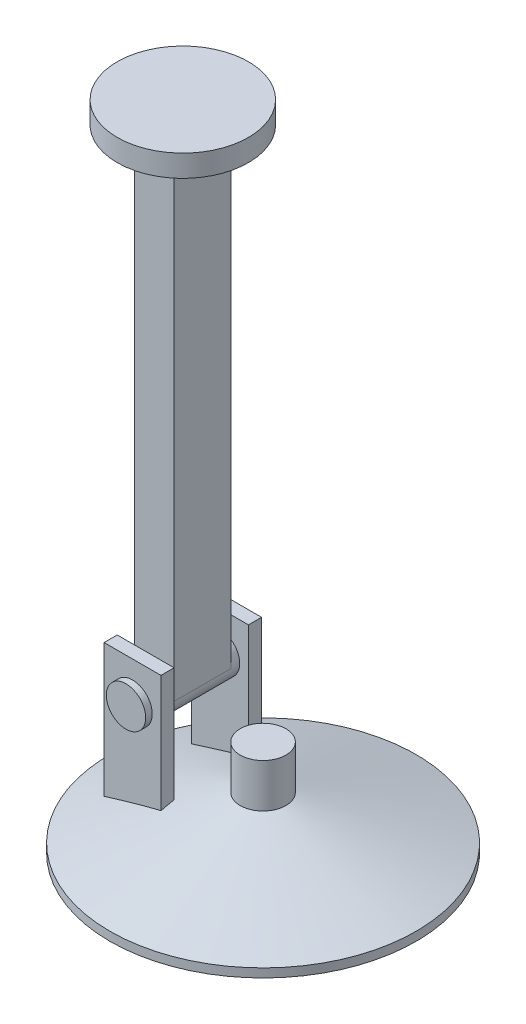
SolidWorks part; units mm, degrees
ref_plane "Front Plane" through (0, 0, 0) normal (0, 0, 1) x (1, 0, 0)
ref_plane "Top Plane" through (0, 0, 0) normal (0, 1, 0) x (1, 0, 0)
ref_plane "Right Plane" through (0, 0, 0) normal (1, 0, 0) x (0, 0, -1)
sketch "Sketch1" plane through (0, 0, 0) normal (0, 1, 0) x (1, 0, 0)
  circle A0 centre (0, 0) radius 35
  point P3 (0, 0)
  point P4 (0, 0)
  dimension "D1" = 70
ref_plane "Plane1" through (0, 10, 0) normal (0, 1, 0) x (1, 0, 0)
sketch "Sketch2" plane through (0, 10, 0) normal (0, 1, 0) x (1, 0, 0)
  circle A0 centre (0, 0) radius 5.2243
loft "Loft3" add profiles "Sketch1", "Sketch2"
sketch "Sketch8" plane through (0, 10, 0) normal (0, 1, 0) x (1, 0, 0)
  circle A0 centre (0, 0) radius 5.2243
extrude "Boss-Extrude1" add sketch "Sketch8" along normal blind 10
sketch "Sketch10" plane through (0, 0, 0) normal (0, 1, 0) x (1, 0, 0)
  circle A0 centre (0, 0) radius 35
ref_plane "Plane2" through (0, 0, 10) normal (0, 0, 1) x (1, 0, 0)
sketch "Sketch16" plane through (0, 0, 10) normal (0, 0, 1) x (1, 0, 0)
  line L0 (35, 0) -> (-35, 0) construction
  line L1 (-24.8409, 0) -> (-11.8409, 0)
  line L2 (-24.8409, 0) -> (-24.8409, 33)
  line L3 (-24.8409, 33) -> (-11.8409, 33)
  line L4 (-11.8409, 0) -> (-11.8409, 33)
  dimension "D1" = 33
  dimension "D2" = 13
extrude "Boss-Extrude5" add sketch "Sketch16" along normal mid plane 3
mirror "Mirror2" about plane through (0, 0, 0) normal (0, 0, 1) of "Boss-Extrude5"
sketch "Sketch19" plane through (0, 0, 0) normal (0, 0, 1) x (1, 0, 0)
  line L0 (-11.8409, 6.211) -> (-11.8409, 33) construction
  circle A0 centre (-18.3409, 24.3425) radius 4.5
  dimension "D1" = 9
  dimension "D2" = 6.5
extrude "Boss-Extrude6" add sketch "Sketch19" along normal mid plane 26
sketch "Sketch21" plane through (0, 0, 0) normal (0, 0, 1) x (1, 0, 0)
  line L1 (-22.8409, 24.3425) -> (-13.8409, 24.3425)
  line L2 (-22.8409, 24.3425) -> (-22.8409, 133.0025)
  line L3 (-22.8409, 133.0025) -> (-13.8409, 133.0025)
  line L4 (-13.8409, 24.3425) -> (-13.8409, 133.0025)
  circle A0 centre (-18.3409, 24.3425) radius 4.5 construction
  circle A1 centre (-18.3409, 24.3425) radius 4.5 construction
  dimension "D1" = 108.66
extrude "Boss-Extrude7" add sketch "Sketch21" along normal mid plane 13
sketch "Sketch22" plane through (0, 0, 0) normal (0, 1, 0) x (1, 0, 0)
  circle A0 centre (0, 0) radius 35
  dimension "D1" = 70
extrude "Boss-Extrude8" add sketch "Sketch22" against normal blind 2
sketch "Sketch23" plane through (0, 133.0025, 0) normal (0, 1, 0) x (1, 0, 0)
  line L0 (-18.3409, -6.5) -> (-18.3409, 6.5) construction
  line L1 (-13.8409, -6.5) -> (-22.8409, -6.5) construction
  line L2 (-13.8409, 6.5) -> (-22.8409, 6.5) construction
  line L3 (-22.8409, 0) -> (-13.8409, 0) construction
  line L4 (-22.8409, -6.5) -> (-22.8409, 6.5) construction
  line L5 (-13.8409, -6.5) -> (-13.8409, 6.5) construction
  circle A0 centre (-18.3409, 0) radius 15
  dimension "D1" = 30
extrude "Boss-Extrude9" add sketch "Sketch23" along normal blind 5
